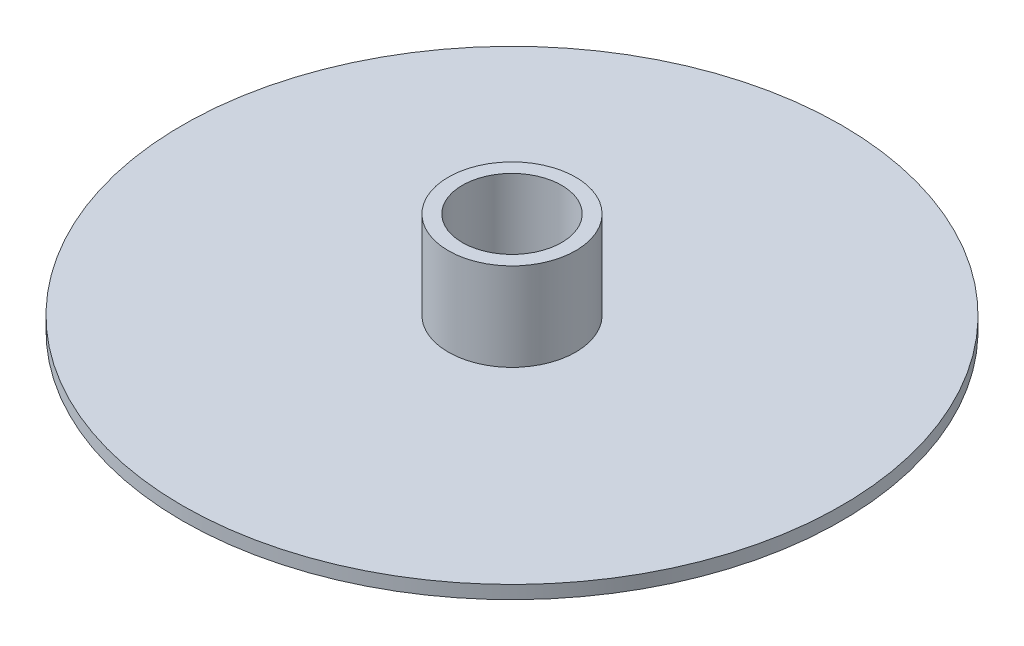
SolidWorks part; units mm, degrees
ref_plane "Front Plane" through (0, 0, 0) normal (0, 0, 1) x (1, 0, 0)
ref_plane "Top Plane" through (0, 0, 0) normal (0, 1, 0) x (1, 0, 0)
ref_plane "Right Plane" through (0, 0, 0) normal (1, 0, 0) x (0, 0, -1)
sketch "Sketch1" plane through (0, 0, 0) normal (0, 1, 0) x (1, 0, 0)
  circle A0 centre (0, 0) radius 75
  dimension "D1" = 150
extrude "Boss-Extrude1" add sketch "Sketch1" along normal blind 3
sketch "Sketch2" plane through (0, 3, 0) normal (0, 1, 0) x (1, 0, 0)
  circle A0 centre (0, 0) radius 14.5
  circle A1 centre (0, 0) radius 11.3
  dimension "D1" = 29
  dimension "D2" = 3.2
extrude "Boss-Extrude2" add sketch "Sketch2" along normal blind 20
fillet "Fillet1" radius 3 1 edges at (0, 3, 11.3)
